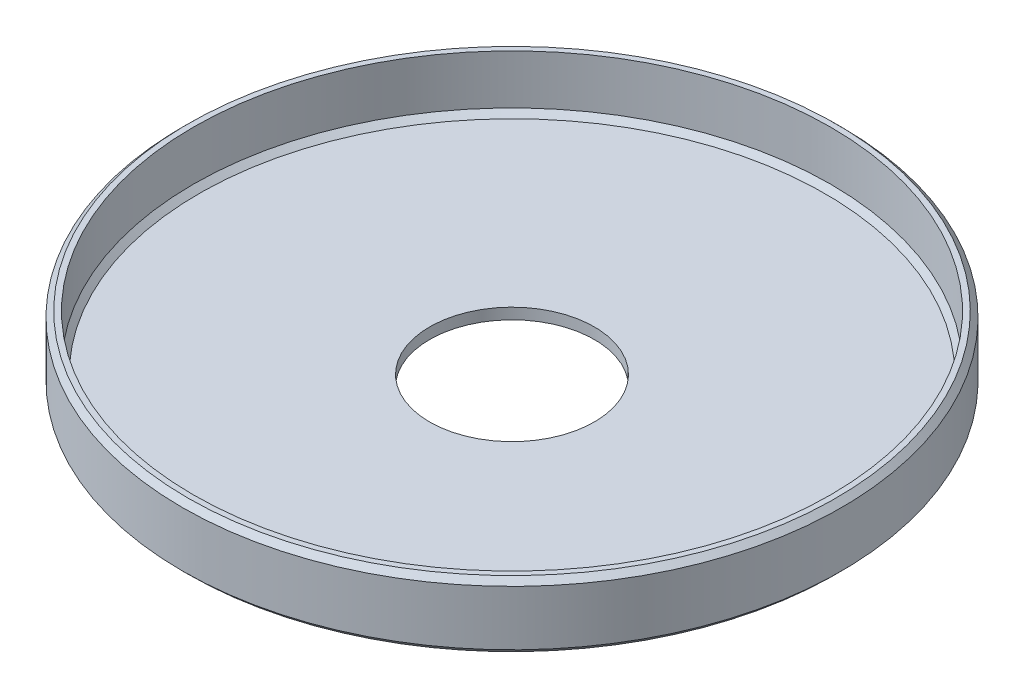
SolidWorks part; units mm, degrees
ref_plane "Přední rovina" through (0, 0, 0) normal (0, 0, 1) x (1, 0, 0)
ref_plane "Horní rovina" through (0, 0, 0) normal (0, 1, 0) x (1, 0, 0)
ref_plane "Pravá rovina" through (0, 0, 0) normal (1, 0, 0) x (0, 0, -1)
sketch "Skica1" plane through (0, 0, 0) normal (0, 1, 0) x (1, 0, 0)
  circle A0 centre (0, 0) radius 60
  circle A1 centre (0, 0) radius 15
  dimension "D1" = 120
  dimension "D2" = 30
extrude "Přidat vysunutím1" add sketch "Skica1" along normal blind 2
sketch "Skica2" plane through (0, 2, 0) normal (0, 1, 0) x (1, 0, 0)
  circle A0 centre (0, 0) radius 60
  circle A1 centre (0, 0) radius 58
  dimension "D1" = 120
  dimension "D2" = 116
extrude "Přidat vysunutím2" add sketch "Skica2" along normal blind 10
chamfer "Zkosení1" distance 1 angle 45 1 edges at (0, 2, 58)
chamfer "Zkosení2" distance 1 angle 45 1 edges at (0, 0, 60)
chamfer "Zkosení3" distance 1 angle 45 1 edges at (0, 12, 60)
